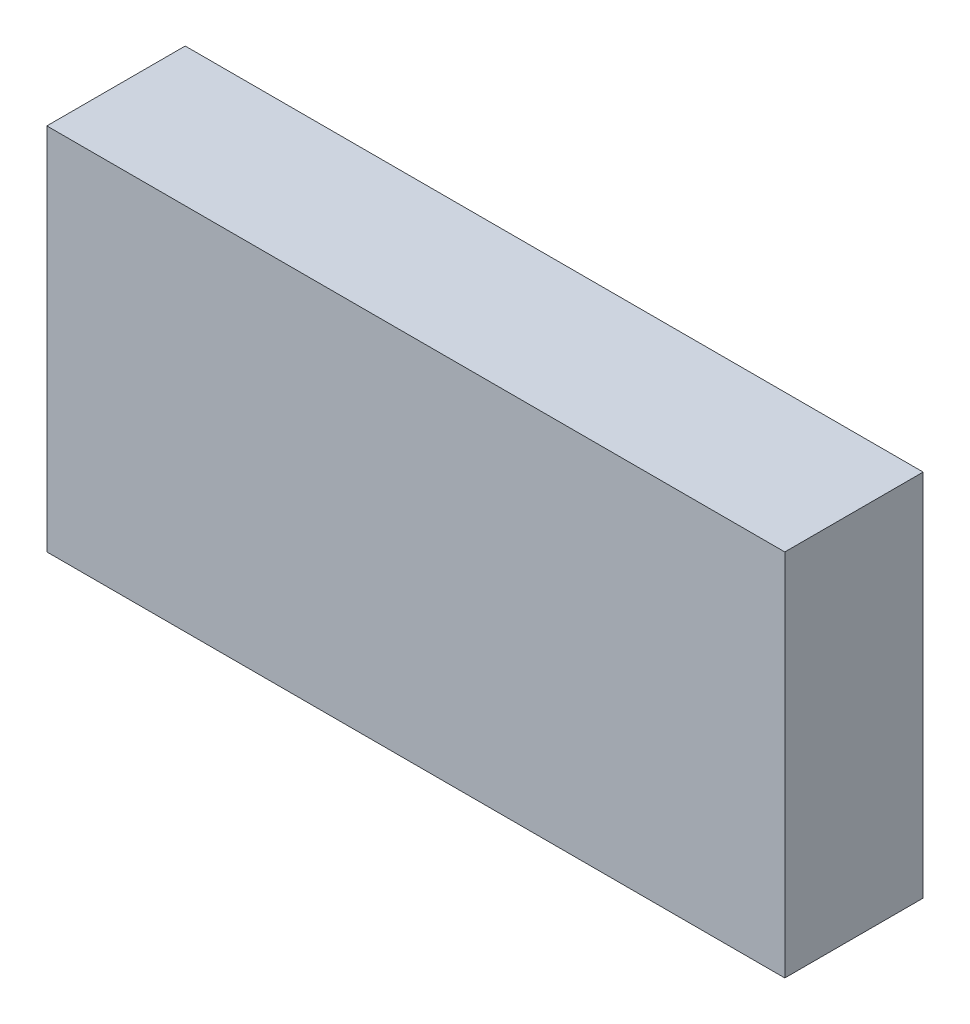
SolidWorks part; units mm, degrees
ref_plane "Front Plane" through (0, 0, 0) normal (0, 0, 1) x (1, 0, 0)
ref_plane "Top Plane" through (0, 0, 0) normal (0, 1, 0) x (1, 0, 0)
ref_plane "Right Plane" through (0, 0, 0) normal (1, 0, 0) x (0, 0, -1)
sketch "Sketch1" plane through (0, 0, 0) normal (0, 0, 1) x (1, 0, 0)
  line L1 (-40, -20) -> (40, -20)
  line L2 (-40, -20) -> (-40, 20)
  line L3 (-40, 20) -> (40, 20)
  line L4 (40, -20) -> (40, 20)
  line L5 (-40, -20) -> (40, 20) construction
  line L6 (-40, 20) -> (40, -20) construction
  point P0 (0, 0)
  dimension "D1" = 40
  dimension "D2" = 80
extrude "Boss-Extrude1" add sketch "Sketch1" along normal blind 15
sketch "Sketch2" plane through (0, 0, 15) normal (0, 0, 1) x (1, 0, 0)
  line L1 (-40, -20) -> (40, -20) construction
  line L2 (0, 0) -> (0, -50000) construction
  circle A0 centre (0, -14) radius 12
  circle A1 centre (25.5348, -14) radius 12
  circle A2 centre (0, -14) radius 11 construction
  circle A3 centre (25.5348, -14) radius 11 construction
  circle A4 centre (-26.9502, -14) radius 12
  circle A5 centre (-26.9502, -14) radius 11 construction
  point P7 (0, -26)
  point P15 (0, 0)
  point P16 (0, 0)
  dimension "D1" = 24
  dimension "D2" = 6
